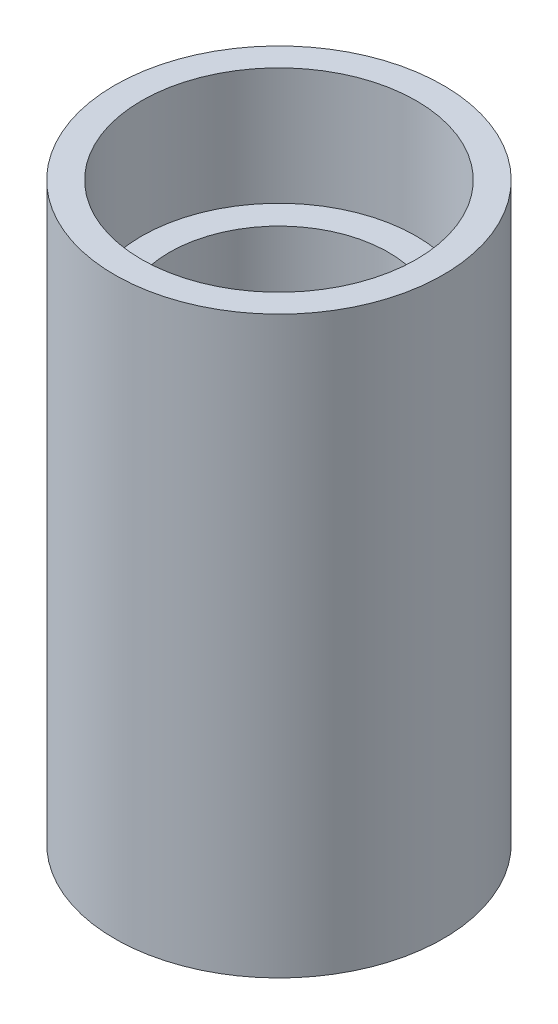
SolidWorks part; units mm, degrees
material "6061-T6 (SS)"
ref_plane "Front Plane" through (0, 0, 0) normal (0, 0, 1) x (1, 0, 0)
ref_plane "Top Plane" through (0, 0, 0) normal (0, 1, 0) x (1, 0, 0)
ref_plane "Right Plane" through (0, 0, 0) normal (1, 0, 0) x (0, 0, -1)
sketch "Sketch1" plane through (0, 0, 0) normal (0, 0, 1) x (1, 0, 0)
  line L0 (0, 55.7468) -> (0, -29.699) construction
  line L2 (25.4, 0) -> (38.1, 0)
  line L3 (25.4, 0) -> (25.4, 106.1466)
  line L4 (31.877, 133.35) -> (38.1, 133.35)
  line L5 (38.1, 0) -> (38.1, 133.35)
  line L8 (25.4, 106.1466) -> (31.877, 106.1466)
  line L9 (31.877, 133.35) -> (31.877, 106.1466)
  dimension "D1" = 76.2
  dimension "D2" = 12.7
  dimension "D3" = 133.35
  dimension "D4" = 27.2034
  dimension "D5" = 63.754
revolve "Revolve1" add sketch "Sketch1" angle 360 about L0
